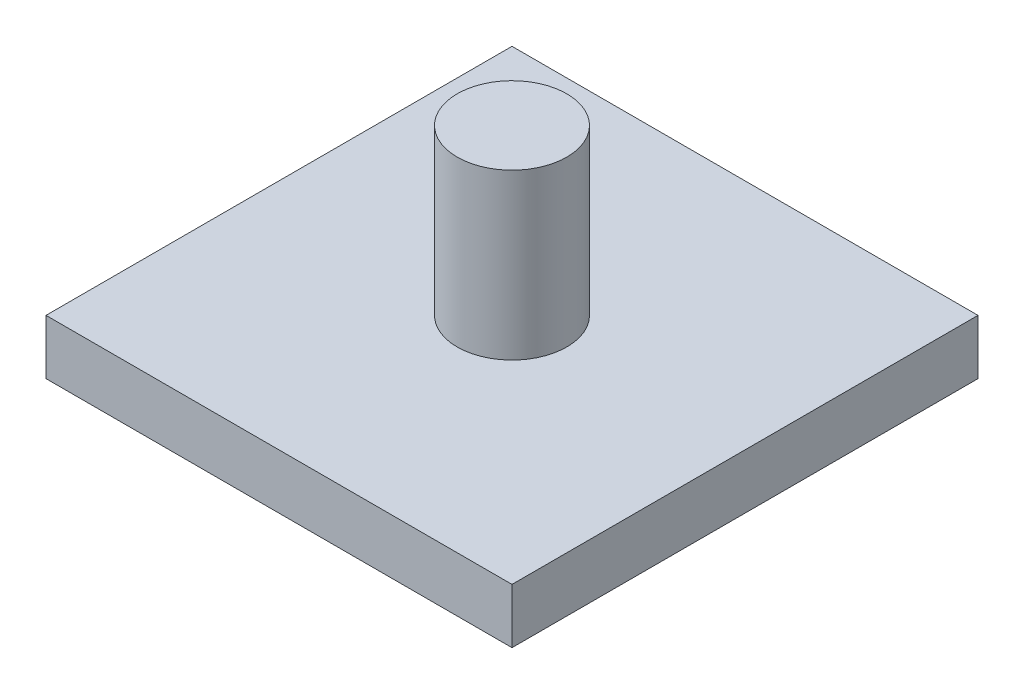
SolidWorks part; units mm, degrees
ref_plane "Front Plane" through (0, 0, 0) normal (0, 0, 1) x (1, 0, 0)
ref_plane "Top Plane" through (0, 0, 0) normal (0, 1, 0) x (1, 0, 0)
ref_plane "Right Plane" through (0, 0, 0) normal (1, 0, 0) x (0, 0, -1)
sketch "Sketch2" plane through (0, 0, 0) normal (0, 1, 0) x (1, 0, 0)
  line L1 (-5.9549, 7.5981) -> (11.0451, 7.5981)
  line L2 (-5.9549, 7.5981) -> (-5.9549, -9.4019)
  line L3 (-5.9549, -9.4019) -> (11.0451, -9.4019)
  line L4 (11.0451, 7.5981) -> (11.0451, -9.4019)
  dimension "D1" = 17
  dimension "D2" = 17
extrude "Boss-Extrude1" add sketch "Sketch2" along normal blind 2
sketch "Sketch3" plane through (0, 2, 0) normal (0, 1, 0) x (1, 0, 0)
  line L0 (2.5451, 7.5981) -> (2.5451, -9.4019) construction
  line L1 (11.0451, 7.5981) -> (-5.9549, 7.5981) construction
  line L2 (-5.9549, -9.4019) -> (11.0451, -9.4019) construction
  line L3 (-5.9549, -0.9019) -> (11.0451, -0.9019) construction
  line L4 (-5.9549, 7.5981) -> (-5.9549, -9.4019) construction
  line L5 (11.0451, -9.4019) -> (11.0451, 7.5981) construction
  circle A0 centre (2.5451, -0.9019) radius 2
  dimension "D1" = 4
extrude "Boss-Extrude2" add sketch "Sketch3" along normal blind 6
